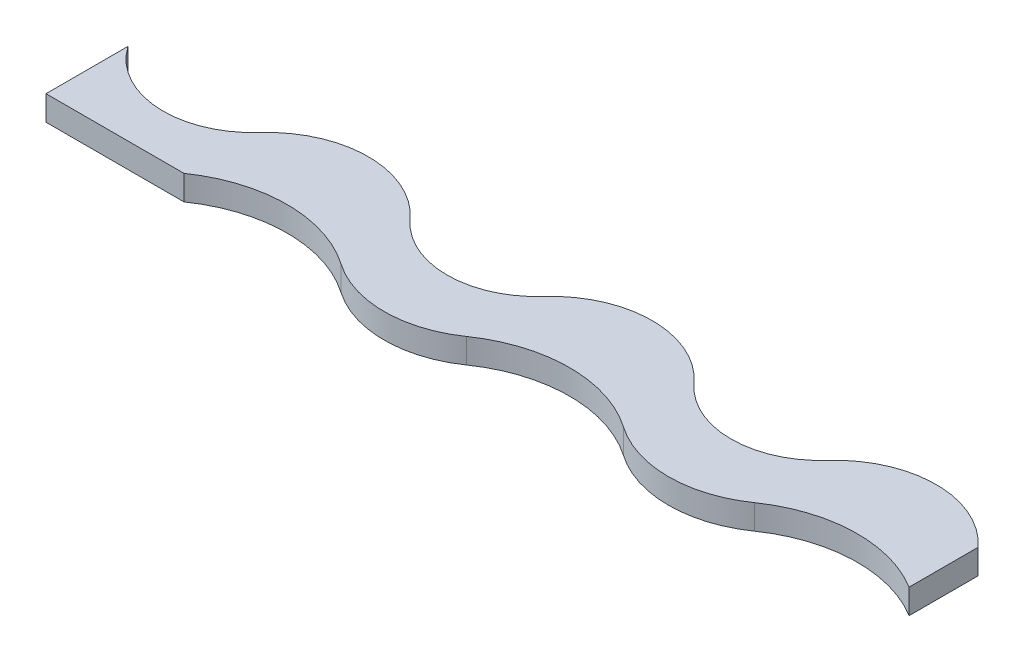
SolidWorks part; units mm, degrees
material "5052-H32"
ref_plane "Front Plane" through (0, 0, 0) normal (0, 0, 1) x (1, 0, 0)
ref_plane "Top Plane" through (0, 0, 0) normal (0, 1, 0) x (1, 0, 0)
ref_plane "Right Plane" through (0, 0, 0) normal (1, 0, 0) x (0, 0, -1)
sketch "Sketch2" plane through (0, 0, 0) normal (0, 1, 0) x (1, 0, 0)
  line L0 (11.15, 0) -> (0, 0) construction
  line L1 (0, 0) -> (0, 6.63)
  line L2 (0, 0) -> (11.15, 0)
  line L3 (69.4199, 0.343) -> (69.4199, 5.91)
  arc A0 (11.3467, 5.91) -> (0, 6.63) centre (5.9583, 10.7605) cw
  arc A1 (11.3467, 5.91) -> (23.5199, 5.91) centre (17.4333, 0.431) cw
  arc A2 (23.5199, 5.91) -> (34.2967, 5.91) centre (28.9083, 10.7605) ccw
  arc A3 (11.15, 0) -> (23.8477, 0) centre (17.4989, -9.1355) cw
  arc A4 (23.8477, 0) -> (33.9831, 0) centre (28.9154, 7.292) ccw
  arc A5 (34.2967, 5.91) -> (46.4699, 5.91) centre (40.3833, 0.431) cw
  arc A6 (33.9831, 0) -> (46.6808, 0) centre (40.3319, -9.1355) cw
  arc A7 (46.6808, 0) -> (57.2467, 0) centre (51.9637, 7.6018) ccw
  arc A8 (57.2467, 0) -> (69.4199, 0.343) centre (63.5956, -9.1355) cw
  arc A9 (46.4699, 5.91) -> (57.2467, 5.91) centre (51.8583, 10.7605) ccw
  arc A10 (57.2467, 5.91) -> (69.4199, 5.91) centre (63.3333, 0.431) cw
  circle A11 centre (5.9583, 10.7605) radius 7
  circle A12 centre (17.4989, -9.1355) radius 10.875
  circle A13 centre (28.9083, 10.7605) radius 7
  circle A14 centre (51.8583, 10.7605) radius 7
  circle A15 centre (40.3319, -9.1355) radius 10.875
  circle A16 centre (63.5956, -9.1355) radius 10.875
  dimension "D1" = 7.25
  dimension "D2" = 11.125
  dimension "D3" = 14
  dimension "D6" = 14
  dimension "D9" = 21.75
  dimension "D11" = 8.88
  dimension "D12" = 14
  dimension "D4" = 6.63
  dimension "D5" = 11.15
  dimension "D7" = 12.3
  dimension "D8" = 0.72
  dimension "D10" = 19.74
  dimension "D13" = 22.95
extrude "Boss-Extrude1" add sketch "Sketch2" along normal blind 2 contours L1 A0 A1 A2 A5 A9 A10 L3 A8 A7 A6 A4 A3 L2
